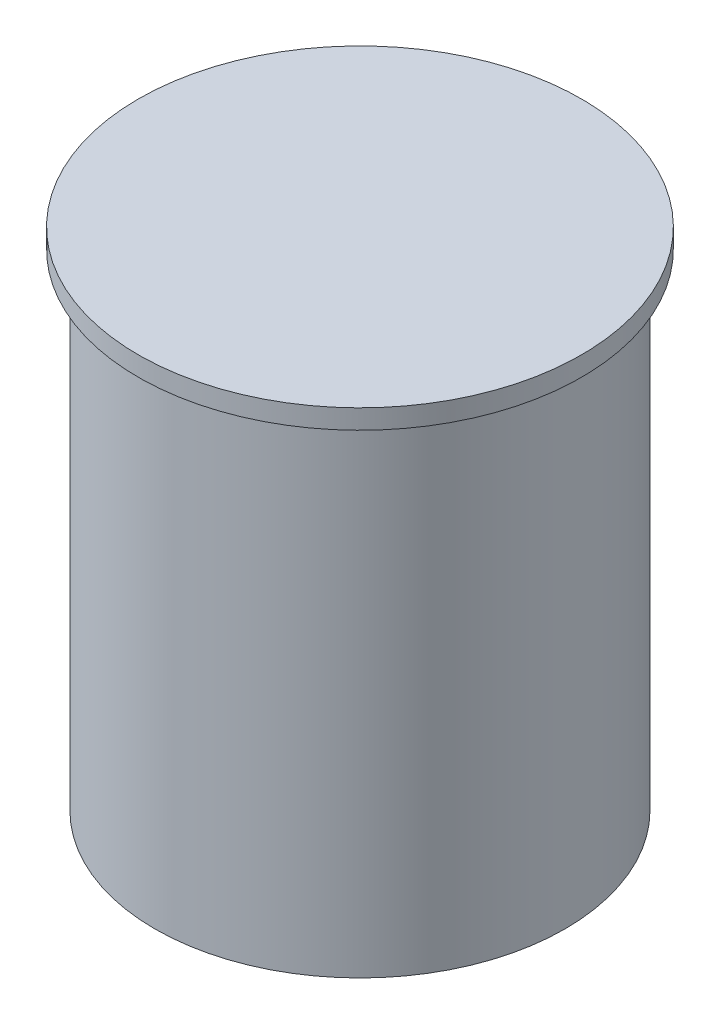
SolidWorks part; units mm, degrees
ref_plane "Front Plane" through (0, 0, 0) normal (0, 0, 1) x (1, 0, 0)
ref_plane "Top Plane" through (0, 0, 0) normal (0, 1, 0) x (1, 0, 0)
ref_plane "Right Plane" through (0, 0, 0) normal (1, 0, 0) x (0, 0, -1)
sketch "Sketch1" plane through (0, 0, 0) normal (0, 0, 1) x (1, 0, 0)
  line L0 (0, 0) -> (28.956, 0)
  line L1 (0, 0) -> (0, -66.04) construction
  line L2 (28.956, 0) -> (28.956, -2.54)
  line L3 (0, -66.04) -> (26.797, -66.04)
  line L4 (26.797, -66.04) -> (26.797, -2.54)
  line L5 (26.797, -2.54) -> (28.956, -2.54)
  line L6 (0, -66.04) -> (0, -63.5)
  line L7 (0, 0) -> (0, -2.54)
  line L8 (0, -2.54) -> (24.257, -2.54)
  line L9 (0, -63.5) -> (24.257, -63.5)
  line L10 (24.257, -63.5) -> (24.257, -2.54)
  dimension "D1" = 28.956
  dimension "D2" = 2.54
  dimension "D3" = 63.5
  dimension "D4" = 26.797
revolve "Revolve1" add sketch "Sketch1" angle 360 about L1
